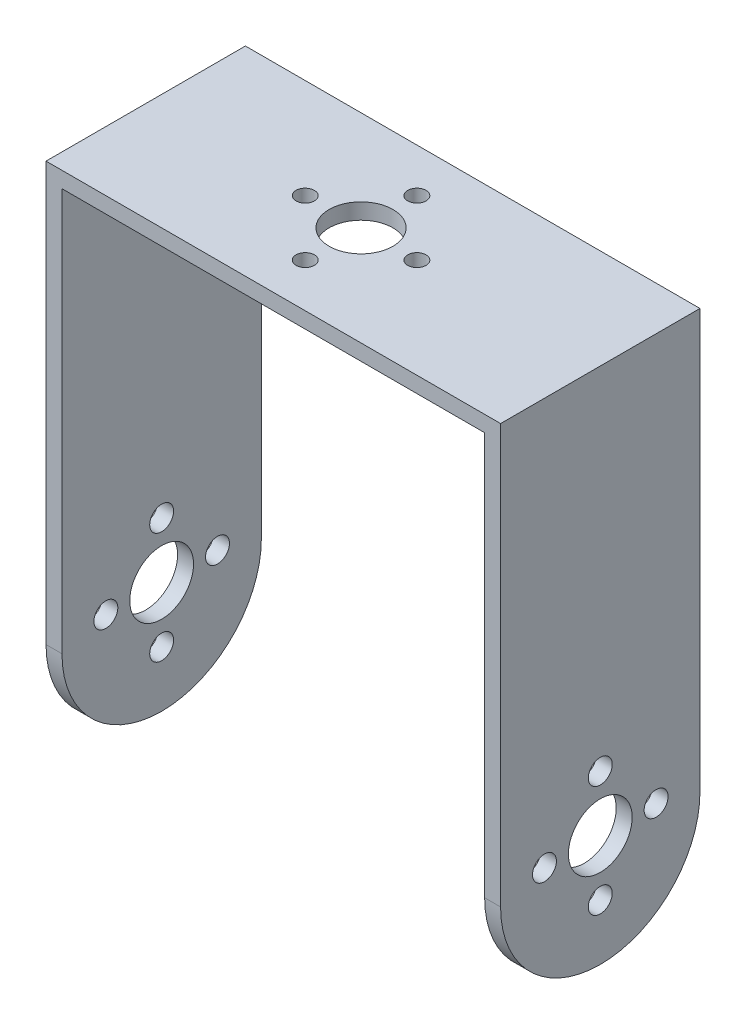
SolidWorks part; units mm, degrees
material "1060 Alloy"
ref_plane "Front Plane" through (0, 0, 0) normal (0, 0, 1) x (1, 0, 0)
ref_plane "Top Plane" through (0, 0, 0) normal (0, 1, 0) x (1, 0, 0)
ref_plane "Right Plane" through (0, 0, 0) normal (1, 0, 0) x (0, 0, -1)
sketch "Sketch3" plane through (0, 0, 0) normal (0, 0, 1) x (1, 0, 0)
  line L0 (-79.9255, 45.3865) -> (-27.043, 45.3865)
  line L1 (-81.9255, 45.3865) -> (-79.9255, 45.3865)
  line L2 (-81.9255, 45.3865) -> (-81.9255, -19.6135)
  line L3 (-81.9255, -19.6135) -> (-79.9255, -19.6135)
  line L4 (-79.9255, 43.39) -> (-79.9255, -19.6135)
  line L5 (-81.9255, 45.3865) -> (-79.9255, -19.6135) construction
  line L6 (-81.9255, -19.6135) -> (-79.9255, 45.3865) construction
  line L7 (-79.9255, 43.39) -> (-26.9255, 43.39)
  line L8 (-26.9255, 43.39) -> (-26.9255, -19.6135)
  line L9 (-27.043, 45.3865) -> (-24.9255, 45.3865)
  line L10 (-26.9255, -19.6135) -> (-24.9255, -19.6135)
  line L11 (-24.9255, 45.3865) -> (-24.9255, -19.6135)
  point P0 (-80.9255, 12.8865)
  dimension "D1" = 65
  dimension "D2" = 2
  dimension "D3" = 2
  dimension "D4" = 57
  dimension "D5" = 2
extrude "Boss-Extrude2" add sketch "Sketch3" along normal blind 25
sketch "Sketch4" plane through (0, 45.3865, 0) normal (0, 1, 0) x (1, 0, 0)
  line L0 (-81.9255, -25) -> (-81.9255, 0) construction
  line L3 (-24.9255, -25) -> (-81.9255, -25) construction
  circle A0 centre (-54.9255, -12.5) radius 4
  dimension "D1" = 27
  dimension "D2" = 12.5
extrude "Cut-Extrude1" cut sketch "Sketch4" against normal through all
sketch "Sketch6" plane through (-81.9255, 0, 0) normal (-1, 0, 0) x (0, 0, 1)
  line L1 (25, 45.3865) -> (0, 45.3865) construction
  line L2 (0, 45.3865) -> (0, -19.6135) construction
  circle A0 centre (12.5, -5.6135) radius 4
  dimension "D1" = 51
  dimension "D2" = 12.5
extrude "Cut-Extrude2" cut sketch "Sketch6" against normal through all
sketch "Sketch8" plane through (-81.9255, 0, 0) normal (-1, 0, 0) x (0, 0, 1)
  line L0 (25, 45.3865) -> (25, -19.6135) construction
  line L1 (25, -19.6135) -> (0, -19.6135) construction
  line L2 (0, 45.3865) -> (0, -19.6135) construction
  line L3 (25, -19.6135) -> (0, -19.6135)
  line L4 (0, 45.3865) -> (0, -19.6135)
  line L5 (25, 45.3865) -> (25, -19.6135)
  circle A0 centre (12.5, -7.1135) radius 12.5
  line M4 (0, -19.6135) -> (25, -19.6135)
  line M5 (25, -19.6135) -> (25, 45.3865)
extrude "Cut-Extrude3" cut sketch "Sketch8" against normal through all contours A0 L4 M4 | A0 L3 M5
sketch "Sketch9" plane through (-24.9255, 0, 0) normal (1, 0, 0) x (0, 0, -1)
  line L0 (-12.5, -5.6135) -> (-12.5, 1.3865) construction
  circle A0 centre (-12.5, 1.3865) radius 1.5
  circle A2 centre (-5.5, -5.6135) radius 1.5
  circle A3 centre (-12.5, -12.6135) radius 1.5
  circle A4 centre (-19.5, -5.6135) radius 1.5
  point P12 (-12.5, -5.6135)
  point P13 (-12.5, -5.6135)
  dimension "D1" = 4
extrude "Cut-Extrude4" cut sketch "Sketch9" against normal through all
sketch "Sketch10" plane through (0, 45.3865, 0) normal (0, 1, 0) x (1, 0, 0)
  line L0 (-54.9255, -12.5) -> (-54.9255, -19.5) construction
  circle A0 centre (-54.9255, -19.5) radius 1.15
  circle A1 centre (-61.9255, -12.5) radius 1.15
  circle A2 centre (-54.9255, -5.5) radius 1.15
  circle A3 centre (-47.9255, -12.5) radius 1.15
  point P12 (-54.9255, -12.5)
  point P13 (-54.9255, -12.5)
  dimension "D1" = 4
extrude "Cut-Extrude5" cut sketch "Sketch10" against normal through all
